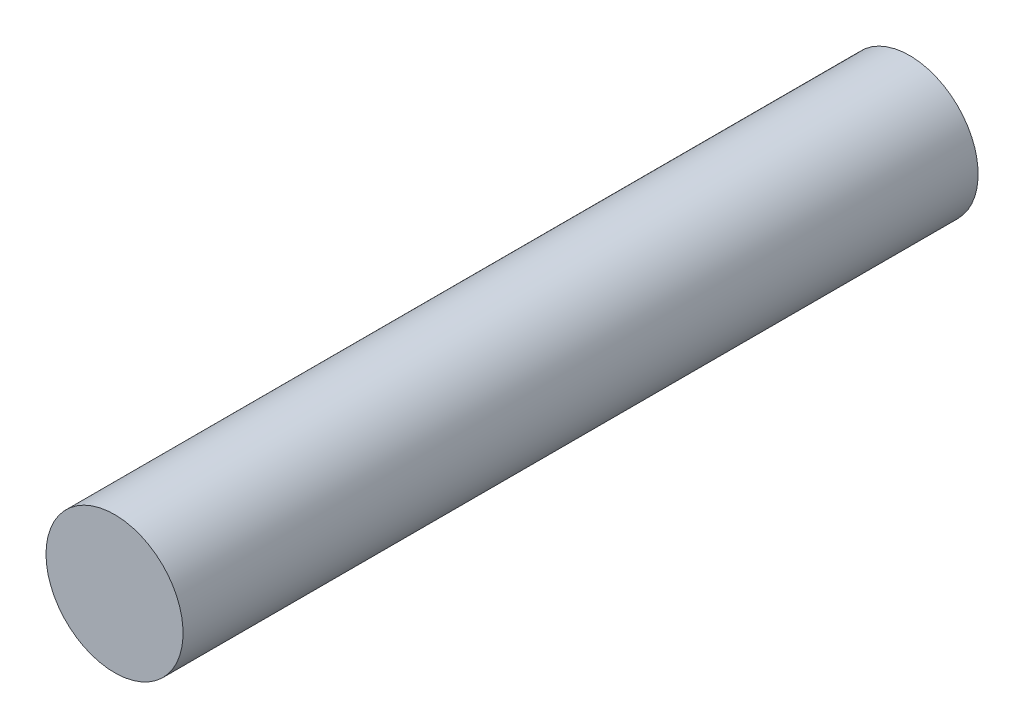
SolidWorks part; units mm, degrees
ref_plane "前视基准面" through (0, 0, 0) normal (0, 0, 1) x (1, 0, 0)
ref_plane "上视基准面" through (0, 0, 0) normal (0, 1, 0) x (1, 0, 0)
ref_plane "右视基准面" through (0, 0, 0) normal (1, 0, 0) x (0, 0, -1)
sketch "草图1" plane through (0, 0, 0) normal (0, 0, 1) x (1, 0, 0)
  circle A0 centre (0, 0) radius 2.5
  dimension "D1" = 5
extrude "凸台-拉伸1" add sketch "草图1" along normal blind 29
